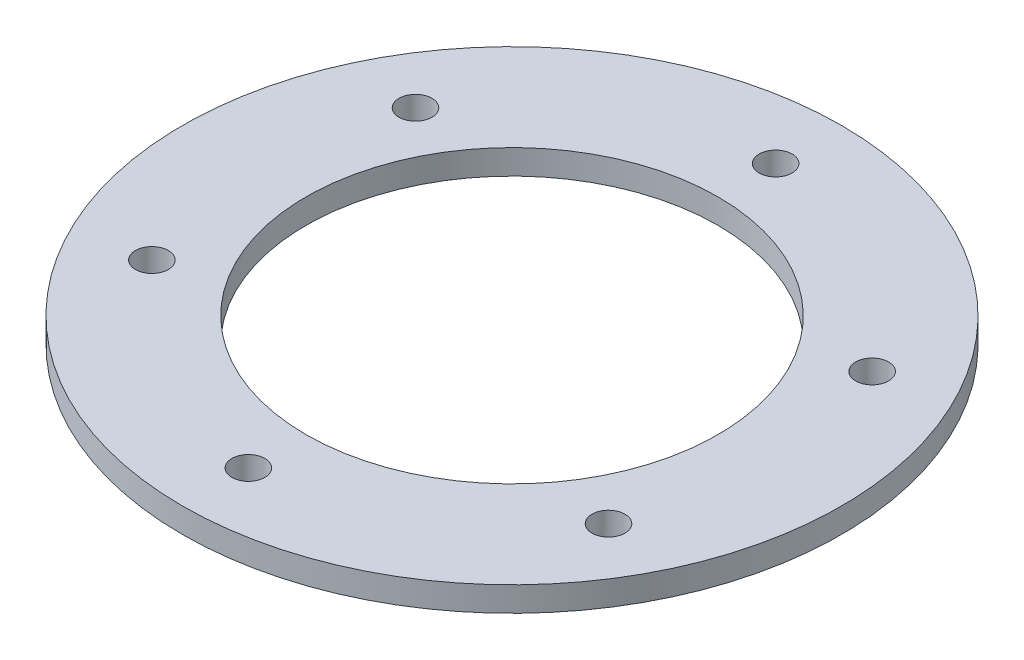
SolidWorks part; units mm, degrees
ref_plane "前基準面" through (0, 0, 0) normal (0, 0, 1) x (1, 0, 0)
ref_plane "上基準面" through (0, 0, 0) normal (0, 1, 0) x (1, 0, 0)
ref_plane "右基準面" through (0, 0, 0) normal (1, 0, 0) x (0, 0, -1)
sketch "草圖2" plane through (0, 0, 0) normal (0, 1, 0) x (1, 0, 0)
  line L0 (0, 129.9031) -> (0, -122.3536) construction
  line L1 (-152.9732, 0) -> (147.5656, 0) construction
  circle A1 centre (0, 0) radius 125
  circle A5 centre (0, 160) radius 10
  circle A6 centre (138.5641, 80) radius 10
  circle A7 centre (138.5641, -80) radius 10
  circle A8 centre (0, -160) radius 10
  circle A9 centre (-138.5641, -80) radius 10
  circle A10 centre (-138.5641, 80) radius 10
  circle A45 centre (0, 0) radius 200
  point P20 (0, 0)
  point P34 (0, 0)
  point P152 (0, 0)
  dimension "D1" = 400
  dimension "D2" = 20
  dimension "D5" = 250
  dimension "D3" = 160
  dimension "D4" = 6
extrude "填料-伸長1" add sketch "草圖2" along normal blind 15
